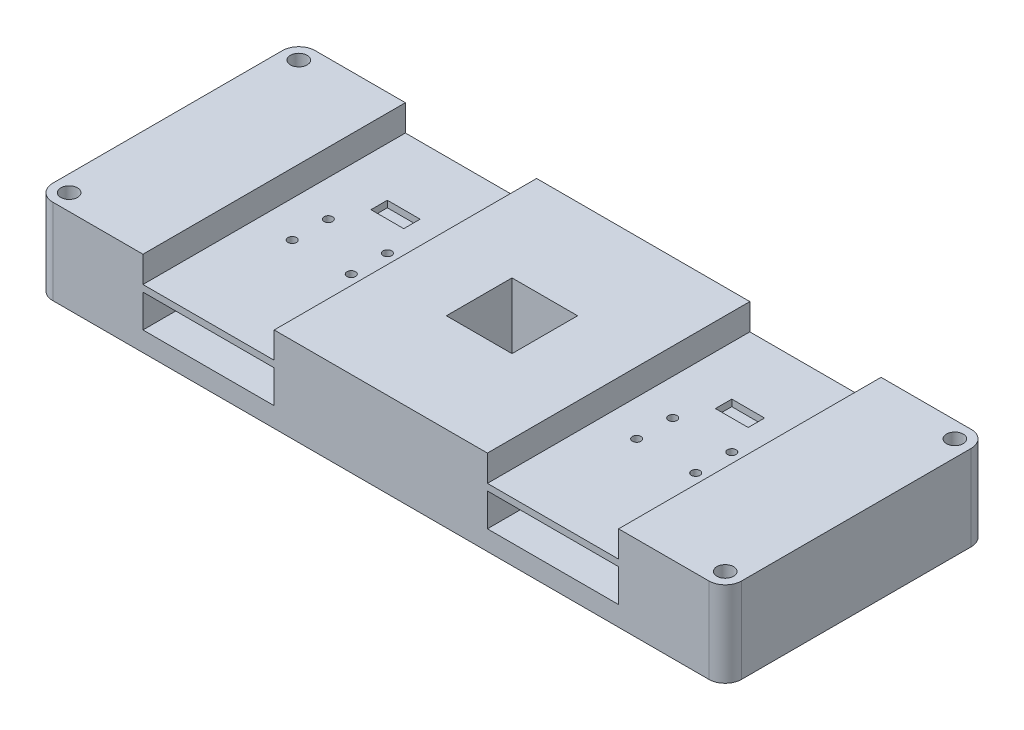
SolidWorks part; units mm, degrees
ref_plane "Front Plane" through (0, 0, 0) normal (0, 0, 1) x (1, 0, 0)
ref_plane "Top Plane" through (0, 0, 0) normal (0, 1, 0) x (1, 0, 0)
ref_plane "Right Plane" through (0, 0, 0) normal (1, 0, 0) x (0, 0, -1)
sketch "Sketch1" plane through (0, 0, 0) normal (0, 1, 0) x (1, 0, 0)
  line L1 (5, 0) -> (205, 0)
  line L2 (0, 5) -> (0, 75)
  line L3 (5, 80) -> (205, 80)
  line L4 (210, 5) -> (210, 75)
  arc A0 (210, 75) -> (205, 80) centre (205, 75) ccw
  arc A1 (210, 5) -> (205, 0) centre (205, 5) cw
  arc A2 (5, 0) -> (0, 5) centre (5, 5) cw
  arc A3 (5, 80) -> (0, 75) centre (5, 75) ccw
  point P7 (210, 80)
  point P10 (210, 0)
  point P13 (0, 0)
  dimension "D3" = 5
  dimension "D1" = 210
  dimension "D2" = 80
extrude "Boss-Extrude1" add sketch "Sketch1" along normal blind 26
sketch "Sketch2" plane through (0, 0, 0) normal (0, 0, 1) x (1, 0, 0)
  line L0 (52.5, 64.5271) -> (52.5, -47.3665) construction
  line L1 (157.5, -47.3665) -> (157.5, 64.5271) construction
  line L2 (0, 26) -> (0, 0) construction
  line L3 (210, 26) -> (210, 0) construction
  line L4 (5, 26) -> (205, 26) construction
  line L5 (32.5, 26) -> (72.5, 26)
  line L6 (32.5, 26) -> (32.5, 6)
  line L7 (32.5, 6) -> (72.5, 6)
  line L8 (72.5, 26) -> (72.5, 6)
  line L10 (137.5, 26) -> (177.5, 26)
  line L11 (137.5, 26) -> (137.5, 6)
  line L12 (137.5, 6) -> (177.5, 6)
  line L13 (177.5, 26) -> (177.5, 6)
  point P14 (52.5, 26)
  point P19 (157.5, 26)
  dimension "D1" = 52.5
  dimension "D2" = 52.5
  dimension "D3" = 20
  dimension "D4" = 40
  dimension "D5" = 20
  dimension "D6" = 40
extrude "Cut-Extrude1" cut sketch "Sketch2" against normal through all
hole_wizard "1/4-20 Tapped Hole1" positions "3DSketch1" profile "Sketch3" tap size "1/4-20" standard "ANSI Inch" end condition through all
sketch3d "3DSketch1"
  line L0 (32.5, 26, -80) -> (5, 26, -80) construction
  line L1 (0, 26, -75) -> (0, 26, -5) construction
  line L2 (177.5, 26, 0) -> (205, 26, 0) construction
  line L3 (210, 26, -5) -> (210, 26, -75) construction
  line L4 (5, 26, 0) -> (32.5, 26, 0) construction
  line L5 (205, 26, -80) -> (177.5, 26, -80) construction
  point P2 (5, 26, -75)
  point P4 (5, 26, -5)
  point P6 (205, 26, -5)
  point P8 (205, 26, -75)
  dimension "D1" = 5
  dimension "D2" = 5
  dimension "D3" = 5
  dimension "D4" = 5
  dimension "D5" = 5
  dimension "D6" = 5
  dimension "D7" = 5
  dimension "D8" = 5
sketch "Sketch3" plane through (5, 26, -75) normal (1, 0, 0) x (0, 0, 1)
  line L0 (0, 0) -> (0, 26)
  line L1 (0, 26) -> (2.5527, 26)
  line L2 (2.5527, 26) -> (2.5527, 0)
  line L5 (2.5527, 0) -> (0, 0)
  line L11 (0, -6.35) -> (0, 107.95) construction
  dimension "Thru Tap Drill Dia." = 5.1054
  dimension "Thru Tap Drill Depth" = 26
cosmetic thread "Hole Thread1" parameters "D2"=6.35
cosmetic thread "Hole Thread2" parameters "D2"=6.35
cosmetic thread "Hole Thread3" parameters "D2"=6.35
cosmetic thread "Hole Thread4" parameters "D2"=6.35
sketch "Sketch4" plane through (0, 26, 0) normal (0, 1, 0) x (1, 0, 0)
  line L0 (0, 0) -> (0, 40) construction
  line L1 (95, 50) -> (115, 50)
  line L2 (95, 50) -> (95, 30)
  line L3 (95, 30) -> (115, 30)
  line L4 (115, 50) -> (115, 30)
  line L5 (0, 75) -> (0, 5) construction
  line L6 (0, 0) -> (105, 0) construction
  line L7 (72.5, 0) -> (137.5, 0) construction
  point P9 (105, 30)
  point P10 (95, 40)
  dimension "D1" = 20
  dimension "D2" = 20
extrude "Cut-Extrude2" cut sketch "Sketch4" against normal through all
sketch "Sketch5" plane through (0, 0, 0) normal (0, 0, 1) x (1, 0, 0)
  line L1 (52.5, 6) -> (52.5, 38.4877) construction
  line L9 (32.5, 18) -> (27.5, 18)
  line L10 (32.5, 26) -> (32.5, 6) construction
  line L11 (27.5, 18) -> (27.5, 13)
  line L12 (27.5, 13) -> (29.5, 13)
  line L13 (29.5, 13) -> (29.5, 16)
  line L14 (29.5, 16) -> (32.5, 16)
  line L16 (5, 26) -> (32.5, 26) construction
  line L17 (32.5, 18) -> (72.5, 18)
  line L18 (32.5, 6) -> (72.5, 6) construction
  line L19 (75.5, 16) -> (72.5, 16)
  line L20 (75.5, 13) -> (75.5, 16)
  line L21 (77.5, 13) -> (75.5, 13)
  line L22 (77.5, 18) -> (77.5, 13)
  line L23 (72.5, 18) -> (77.5, 18)
  line L25 (105, 0) -> (105, 44.8657) construction
  line L26 (32.5, 16) -> (72.5, 16)
  line L27 (5, 0) -> (205, 0) construction
  line L28 (134.5, 13) -> (134.5, 16)
  line L29 (132.5, 13) -> (134.5, 13)
  line L30 (132.5, 18) -> (132.5, 13)
  line L31 (137.5, 18) -> (132.5, 18)
  line L33 (134.5, 16) -> (137.5, 16)
  line L34 (180.5, 16) -> (177.5, 16)
  line L35 (180.5, 13) -> (180.5, 16)
  line L36 (182.5, 13) -> (180.5, 13)
  line L37 (182.5, 18) -> (182.5, 13)
  line L38 (177.5, 18) -> (182.5, 18)
  line L40 (137.5, 18) -> (177.5, 18)
  line L41 (137.5, 16) -> (177.5, 16)
  point P11 (52.5, 22.2439)
  point P15 (52.5, 6)
  point P23 (105, 22.4329)
  point P27 (105, 0)
  dimension "D1" = 5
  dimension "D2" = 3
  dimension "D3" = 5
  dimension "D4" = 8
  dimension "D5" = 2
extrude "Boss-Extrude2" add sketch "Sketch5" against normal up to surface (80 mm away) up to face at (105, 15, -80)
sketch "Sketch6" plane through (0, 18, 0) normal (0, 1, 0) x (1, 0, 0)
  line L0 (0.8624, 40) -> (213.7675, 40) construction
  line L1 (105, 0) -> (105, 80) construction
  line L2 (0, 75) -> (0, 5) construction
  line L3 (52.5, 80) -> (52.5, 0) construction
  line L4 (32.5, 80) -> (72.5, 80) construction
  line L5 (72.5, 0) -> (32.5, 0) construction
  line L6 (157.5, 0) -> (157.5, 80) construction
  line L7 (177.5, 0) -> (137.5, 0) construction
  line L8 (137.5, 80) -> (177.5, 80) construction
  line L9 (72.5, 0) -> (137.5, 0) construction
  line L10 (137.5, 80) -> (72.5, 80) construction
  line L11 (162.5, 54.5) -> (152.5, 54.5)
  line L12 (47.5, 59.5) -> (57.5, 59.5)
  line L13 (47.5, 59.5) -> (47.5, 54.5)
  line L14 (47.5, 54.5) -> (57.5, 54.5)
  line L15 (57.5, 59.5) -> (57.5, 54.5)
  line L16 (152.5, 59.5) -> (152.5, 54.5)
  line L17 (162.5, 59.5) -> (152.5, 59.5)
  line L18 (162.5, 59.5) -> (162.5, 54.5)
  circle A0 centre (43.5, 45.5) radius 1.3
  circle A1 centre (43.5, 34.5) radius 1.3
  circle A2 centre (61.5, 34.5) radius 1.3
  circle A3 centre (61.5, 45.5) radius 1.3
  circle A4 centre (148.5, 34.5) radius 1.3
  circle A5 centre (148.5, 45.5) radius 1.3
  circle A6 centre (166.5, 45.5) radius 1.3
  circle A7 centre (166.5, 34.5) radius 1.3
  point P3 (0, 40)
  point P43 (52.5, 54.5)
  point P44 (57.5, 57)
  dimension "D3" = 2.6
  dimension "D1" = 9
  dimension "D2" = 5.5
  dimension "D4" = 5
  dimension "D5" = 10
  dimension "D6" = 17
extrude "Cut-Extrude3" cut sketch "Sketch6" against normal blind 10
